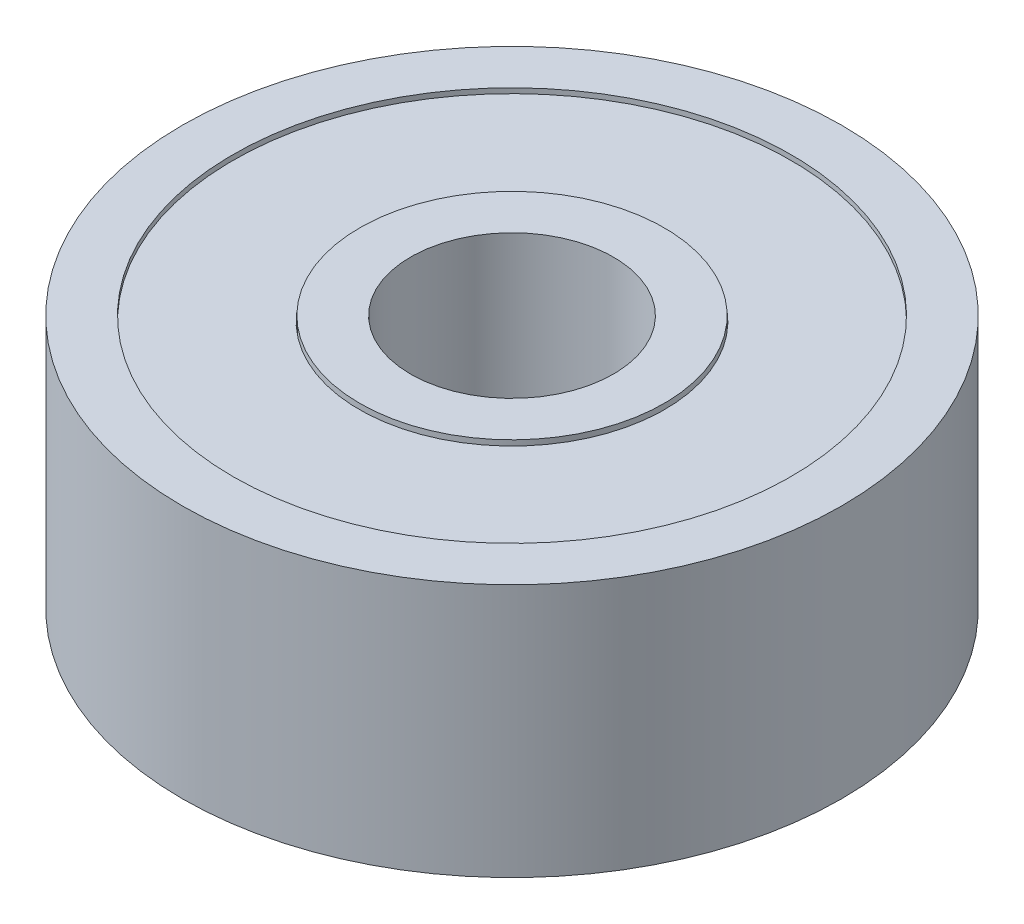
SolidWorks part; units mm, degrees
ref_plane "Front Plane" through (0, 0, 0) normal (0, 0, 1) x (1, 0, 0)
ref_plane "Top Plane" through (0, 0, 0) normal (0, 1, 0) x (1, 0, 0)
ref_plane "Right Plane" through (0, 0, 0) normal (1, 0, 0) x (0, 0, -1)
sketch "Sketch1" plane through (0, 0, 0) normal (0, 1, 0) x (1, 0, 0)
  circle A0 centre (0, 0) radius 6.5
  circle A1 centre (0, 0) radius 2
  dimension "D1" = 13
  dimension "D2" = 4
extrude "Boss-Extrude1" add sketch "Sketch1" along normal blind 5
sketch "Sketch2" plane through (0, 5, 0) normal (0, 1, 0) x (1, 0, 0)
  circle A0 centre (0, 0) radius 5.5
  circle A1 centre (0, 0) radius 6.5 construction
  circle A2 centre (0, 0) radius 3
  circle A3 centre (0, 0) radius 2 construction
  dimension "D1" = 1
  dimension "D2" = 1
extrude "Cut-Extrude1" cut sketch "Sketch2" against normal up to next
sketch "Sketch4" plane through (0, 0, 0) normal (0, -1, 0) x (1, 0, 0)
  circle A2 centre (0, 0) radius 3.01
  circle A3 centre (0, 0) radius 5.99
  dimension "D1" = 6.02
  dimension "D2" = 11.98
extrude "Boss-Extrude2" add sketch "Sketch4" against normal blind 4.8 from offset 0.1 separate body offset against normal yes
